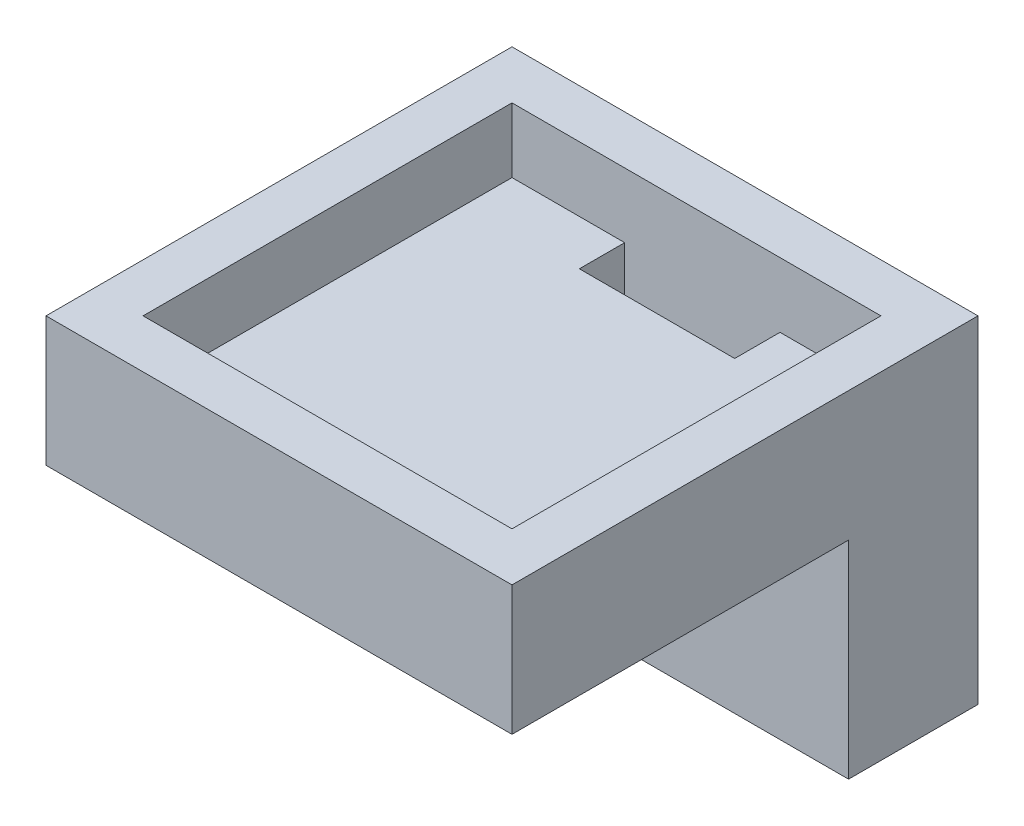
SolidWorks part; units mm, degrees
ref_plane "前基準面" through (0, 0, 0) normal (0, 0, 1) x (1, 0, 0)
ref_plane "上基準面" through (0, 0, 0) normal (0, 1, 0) x (1, 0, 0)
ref_plane "右基準面" through (0, 0, 0) normal (1, 0, 0) x (0, 0, -1)
sketch "草圖1" plane through (0, 0, 0) normal (0, 1, 0) x (1, 0, 0)
  line L1 (-18, 18) -> (18, 18)
  line L2 (-18, 18) -> (-18, -18)
  line L3 (-18, -18) -> (18, -18)
  line L4 (18, 18) -> (18, -18)
  line L5 (-18, 18) -> (18, -18) construction
  line L6 (-18, -18) -> (18, 18) construction
  line L7 (-5.5453, 14.25) -> (6.4547, 14.25)
  line L8 (-5.5453, 14.25) -> (-5.5453, 10.75)
  line L9 (-5.5453, 10.75) -> (6.4547, 10.75)
  line L10 (6.4547, 14.25) -> (6.4547, 10.75)
  line L11 (-5.5453, 14.25) -> (6.4547, 10.75) construction
  line L12 (-5.5453, 10.75) -> (6.4547, 14.25) construction
  point P0 (0, 0)
  point P6 (0.4547, 12.5)
  dimension "D1" = 36
  dimension "D2" = 36
  dimension "D3" = 12
  dimension "D4" = 3.75
  dimension "D5" = 3.5
extrude "填料-伸長1" add sketch "草圖1" along normal blind 5
sketch "草圖2" plane through (0, 0, 0) normal (0, 1, 0) x (1, 0, 0)
  line L1 (-14.25, 14.25) -> (14.25, 14.25)
  line L2 (-14.25, 14.25) -> (-14.25, -14.25)
  line L3 (-14.25, -14.25) -> (14.25, -14.25)
  line L4 (14.25, 14.25) -> (14.25, -14.25)
  line L5 (-14.25, 14.25) -> (14.25, -14.25) construction
  line L6 (-14.25, -14.25) -> (14.25, 14.25) construction
  line L7 (-18, 18) -> (18, 18)
  line L8 (-18, 18) -> (-18, -18)
  line L9 (-18, -18) -> (18, -18)
  line L10 (18, 18) -> (18, -18)
  line L11 (-18, 18) -> (18, -18) construction
  line L12 (-18, -18) -> (18, 18) construction
  point P0 (0, 0)
  point P6 (0, 0)
  dimension "D1" = 28.5
  dimension "D2" = 28.5
extrude "填料-伸長3" add sketch "草圖2" along normal blind 10
sketch "草圖3" plane through (0, 0, 0) normal (0, 1, 0) x (1, 0, 0)
  line L0 (18, -18) -> (18, 18) construction
  line L1 (-18, 18) -> (18, 18)
  line L2 (-18, 18) -> (-18, 8)
  line L3 (-18, 8) -> (18, 8)
  line L4 (18, 18) -> (18, 8)
  line L6 (-5.5453, 14.25) -> (6.4547, 14.25)
  line L7 (-5.5453, 14.25) -> (-5.5453, 10.75)
  line L8 (-5.5453, 10.75) -> (6.4547, 10.75)
  line L9 (6.4547, 14.25) -> (6.4547, 10.75)
  dimension "D1" = 10
extrude "填料-伸長4" add sketch "草圖3" against normal blind 16
